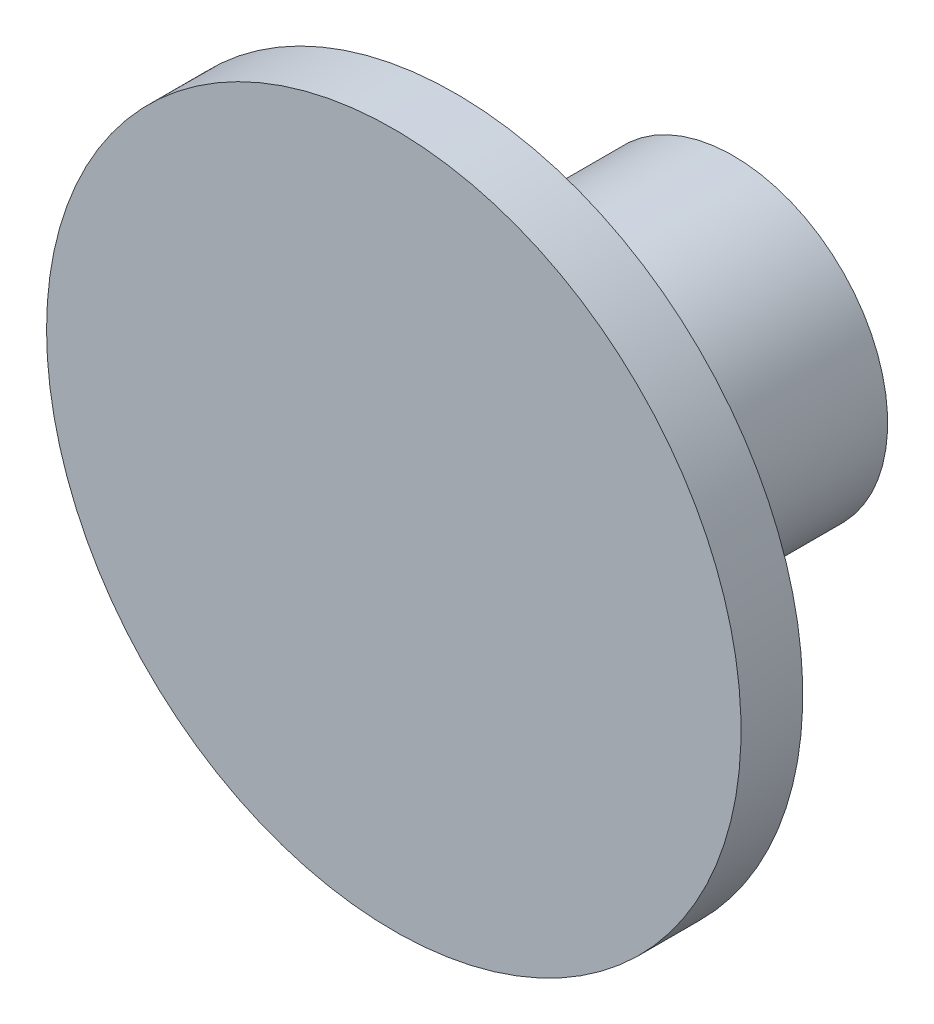
SolidWorks part; units mm, degrees
ref_plane "Front Plane" through (0, 0, 0) normal (0, 0, 1) x (1, 0, 0)
ref_plane "Top Plane" through (0, 0, 0) normal (0, 1, 0) x (1, 0, 0)
ref_plane "Right Plane" through (0, 0, 0) normal (1, 0, 0) x (0, 0, -1)
ref_plane "Plane1" through (0, -10.0526, 0) normal (0, -1, 0) x (1, 0, 0)
sketch "Sketch1" plane through (0, -10.0526, 0) normal (0, -1, 0) x (1, 0, 0)
  line L0 (4.5, -31.5) -> (0, -31.5)
  line L1 (0, -31.5) -> (0, -35.9)
  line L2 (0, -35.9) -> (2, -35.9)
  line L3 (2, -35.9) -> (2, -32.3)
  line L4 (2, -32.3) -> (4.5, -32.3)
  line L5 (4.5, -32.3) -> (4.5, -31.5)
  line L6 (0, -31.5) -> (0, -35.9) construction
revolve "Revolve1" add sketch "Sketch1" angle 360 about L6
